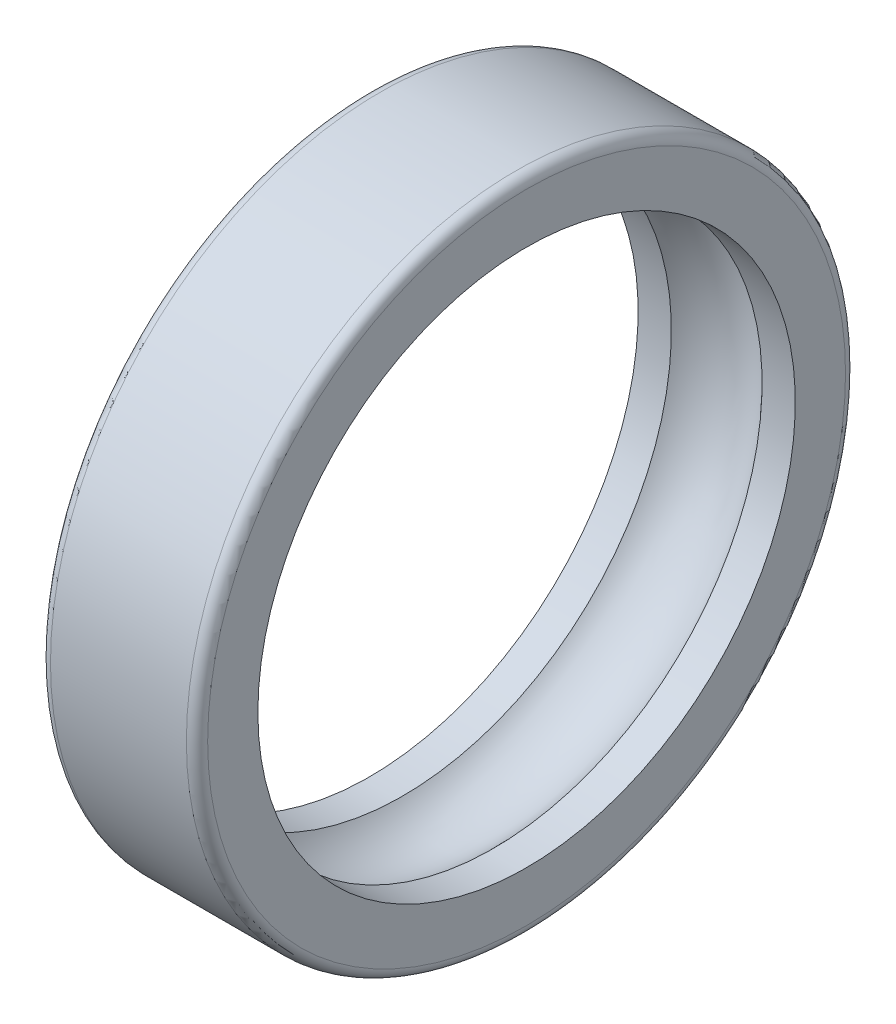
SolidWorks part; units mm, degrees
ref_plane "Front Plane" through (0, 0, 0) normal (0, 0, 1) x (1, 0, 0)
ref_plane "Top Plane" through (0, 0, 0) normal (0, 1, 0) x (1, 0, 0)
ref_plane "Right Plane" through (0, 0, 0) normal (1, 0, 0) x (0, 0, -1)
sketch "Sketch1" plane through (0, 0, 0) normal (0, 0, 1) x (1, 0, 0)
  line L0 (-27.0863, 0) -> (27.0863, 0) construction
  line L1 (0, 0) -> (0, 53) construction
  line L2 (-15.5, 65) -> (15.5, 65)
  line L3 (-15.5, 65) -> (-15.5, 53)
  line L4 (-15.5, 53) -> (-8.9443, 53)
  line L5 (15.5, 65) -> (15.5, 53)
  line L6 (-15.5, 65) -> (15.5, 53) construction
  line L7 (-15.5, 53) -> (15.5, 65) construction
  line L8 (8.9443, 53) -> (15.5, 53)
  arc A0 (-8.9443, 53) -> (8.9443, 53) centre (0, 45) cw
  point P0 (0, 59)
  point P4 (0, 0)
  dimension "D4" = 12
  dimension "D1" = 31
  dimension "D2" = 65
  dimension "D3" = 53
  dimension "D5" = 8
revolve "Revolve1" add sketch "Sketch1" angle 360 about L0
fillet "Fillet1" radius 2.1 2 edges at (15.5, 0, 65) (-15.5, 0, 65)
